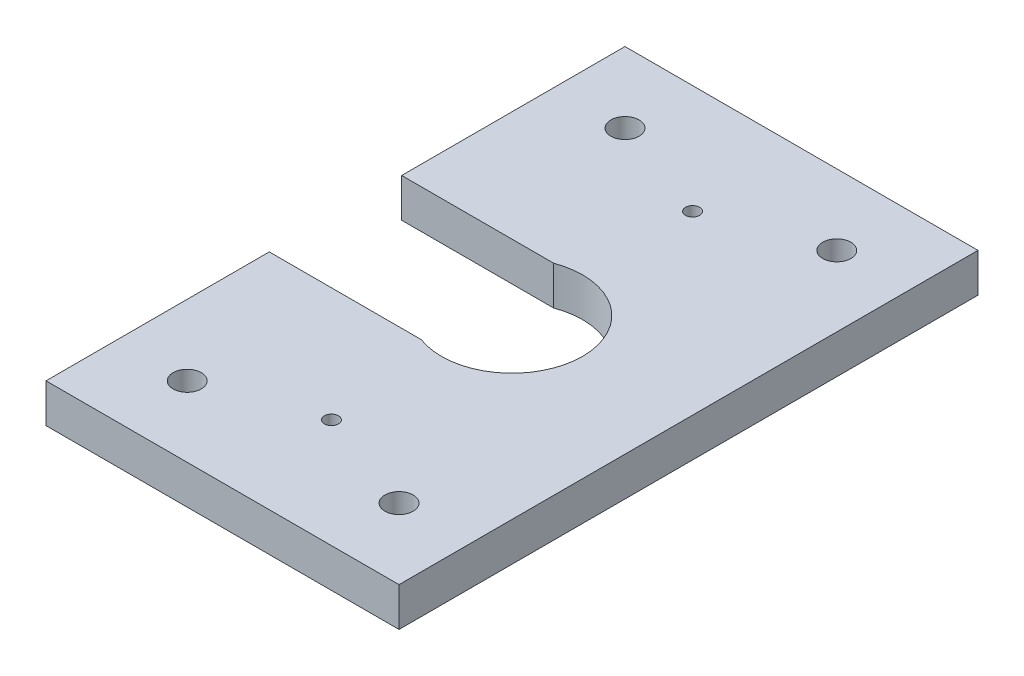
SolidWorks part; units mm, degrees
ref_plane "前视基准面" through (0, 0, 0) normal (0, 0, 1) x (1, 0, 0)
ref_plane "上视基准面" through (0, 0, 0) normal (0, 1, 0) x (1, 0, 0)
ref_plane "右视基准面" through (0, 0, 0) normal (1, 0, 0) x (0, 0, -1)
other "Configuration Table"
sketch "草图1" plane through (0, 0, 0) normal (0, 1, 0) x (1, 0, 0)
  line L1 (0, 0) -> (20, 0)
  line L2 (0, 0) -> (0, -32.8)
  line L3 (0, -32.8) -> (20, -32.8)
  line L4 (20, 0) -> (20, -32.8)
  line L5 (8.6081, -12.65) -> (0, -12.65)
  line L6 (8.6081, -12.65) -> (8.6081, -20.15)
  line L7 (8.6081, -20.15) -> (0, -20.15)
  line L8 (0, -12.65) -> (0, -20.15)
  circle A0 centre (10, -16.4) radius 4
  circle A2 centre (10, -26.63) radius 0.4
  circle A3 centre (10, -6.17) radius 0.4
  circle A4 centre (4, -4) radius 0.8
  circle A5 centre (16, -4) radius 0.8
  circle A6 centre (4, -28.8) radius 0.8
  circle A7 centre (16, -28.8) radius 0.8
  point P8 (10, 0)
  point P18 (0, -16.4)
  dimension "D3" = 8
  dimension "D8" = 0.8
  dimension "D12" = 1.6
  dimension "D1" = 4
  dimension "D2" = 20
  dimension "D4" = 16.4
  dimension "D5" = 7.5
  dimension "D6" = 10.23
  dimension "D7" = 10.23
  dimension "D9" = 4
  dimension "D10" = 4
  dimension "D11" = 4
extrude "凸台-拉伸1" add sketch "草图1" along normal blind 2.2 contours L2 L3 L4 L1 | A0 | L7 L8 L5 L6 | A3 | A2 | A7 | A6 | A4 | A5
